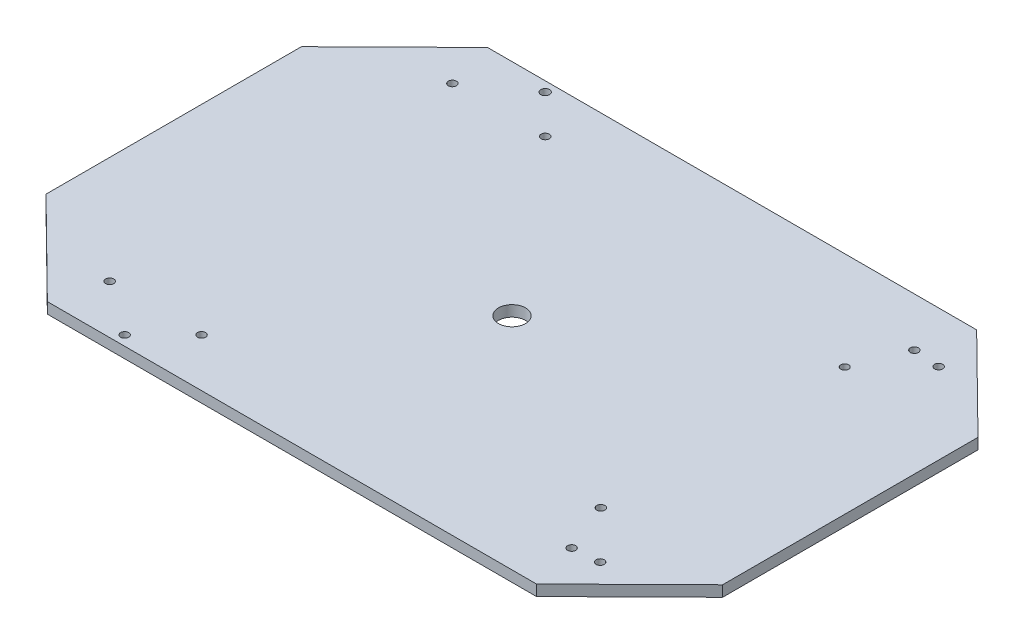
SolidWorks part; units mm, degrees
ref_plane "Alzado" through (0, 0, 0) normal (0, 0, 1) x (1, 0, 0)
ref_plane "Planta" through (0, 0, 0) normal (0, 1, 0) x (1, 0, 0)
ref_plane "Vista lateral" through (0, 0, 0) normal (1, 0, 0) x (0, 0, -1)
sketch "Croquis1" plane through (0, 0, 0) normal (0, 1, 0) x (1, 0, 0)
  line L0 (-90, 81) -> (-124.5, 47)
  line L1 (-124.5, 47) -> (-124.5, 81) construction
  line L2 (-124.5, -47) -> (-124.5, 47)
  line L3 (-124.5, 81) -> (-90, 81) construction
  line L4 (124.5, -47) -> (124.5, 47)
  line L5 (0, 0) -> (103.719, 67.4798) construction
  line L6 (-103.719, 67.4798) -> (0, 0) construction
  line L7 (124.5, 47) -> (90, 81)
  line L8 (0, 0) -> (124.5, 0) construction
  line L9 (0, 0) -> (0, 103.6098) construction
  line L10 (90, 81) -> (124.5, 81) construction
  line L11 (-90, 81) -> (0, 81)
  line L12 (0, 81) -> (90, 81)
  line L13 (124.5, 81) -> (124.5, 47) construction
  line L14 (124.5, -47) -> (90, -81)
  line L15 (-90, -81) -> (0, -81)
  line L16 (-90, -81) -> (-124.5, -47)
  line L17 (0, -81) -> (90, -81)
  point P0 (0, 0)
  point P20 (-124.5, 0)
  dimension "D3" = 180
  dimension "D4" = 47
  dimension "D5" = 47
extrude "Saliente-Extruir1" add sketch "Croquis1" along normal blind 4
sketch "Croquis2" plane through (0, 4, 0) normal (0, 1, 0) x (1, 0, 0)
  line L1 (90, 81) -> (-90, -81) construction
  line L4 (85, -63.0608) -> (-85, -63.0608) construction
  line L5 (85, -63.0608) -> (85, 63.0608) construction
  line L6 (85, 63.0608) -> (-85, 63.0608) construction
  line L7 (-85, -63.0608) -> (-85, 63.0608) construction
  line L8 (85, -63.0608) -> (-85, 63.0608) construction
  line L9 (85, 63.0608) -> (-85, -63.0608) construction
  circle A0 centre (-85, 63.0608) radius 1.5
  circle A1 centre (-85, -63.0608) radius 1.5
  circle A2 centre (85, -63.0608) radius 1.5
  circle A3 centre (85, 63.0608) radius 1.5
  point P8 (0, 0)
  dimension "D1" = 3
  dimension "D2" = 3
  dimension "D3" = 3
  dimension "D4" = 3
  dimension "D5" = 170
extrude "Cortar-Extruir1" cut sketch "Croquis2" against normal blind 10
sketch "Croquis3" plane through (0, 4, 0) normal (0, 1, 0) x (1, 0, 0)
  circle A0 centre (94.7328, -62.2957) radius 1.5
  circle A1 centre (77.5635, -44.8739) radius 1.5
  circle A2 centre (77.5635, 44.8739) radius 1.4391
  circle A3 centre (94.7328, 62.2957) radius 1.5
extrude "Cortar-Extruir2" cut sketch "Croquis3" against normal blind 10
sketch "Croquis4" plane through (0, 0, 0) normal (0, -1, 0) x (1, 0, 0)
  circle A0 centre (-65.1686, -77.3818) radius 1.6209
  circle A1 centre (-51.0265, -63.2397) radius 1.5
  circle A2 centre (-65.1686, 77.3818) radius 1.5
  circle A3 centre (-51.0265, 63.2397) radius 1.5
extrude "Cortar-Extruir3" cut sketch "Croquis4" against normal blind 50
sketch "Croquis5" plane through (0, 4, 0) normal (0, 1, 0) x (1, 0, 0)
  line L0 (-107.25, 64) -> (107.25, -64) construction
  line L1 (-90, 81) -> (-124.5, 47) construction
  line L2 (90, -81) -> (124.5, -47) construction
  line L3 (-107.25, -64) -> (107.25, 64) construction
  line L4 (-124.5, -47) -> (-90, -81) construction
  line L5 (124.5, 47) -> (90, 81) construction
  circle A0 centre (0, 0) radius 5
  dimension "D1" = 10
extrude "Cortar-Extruir4" cut sketch "Croquis5" against normal blind 10
